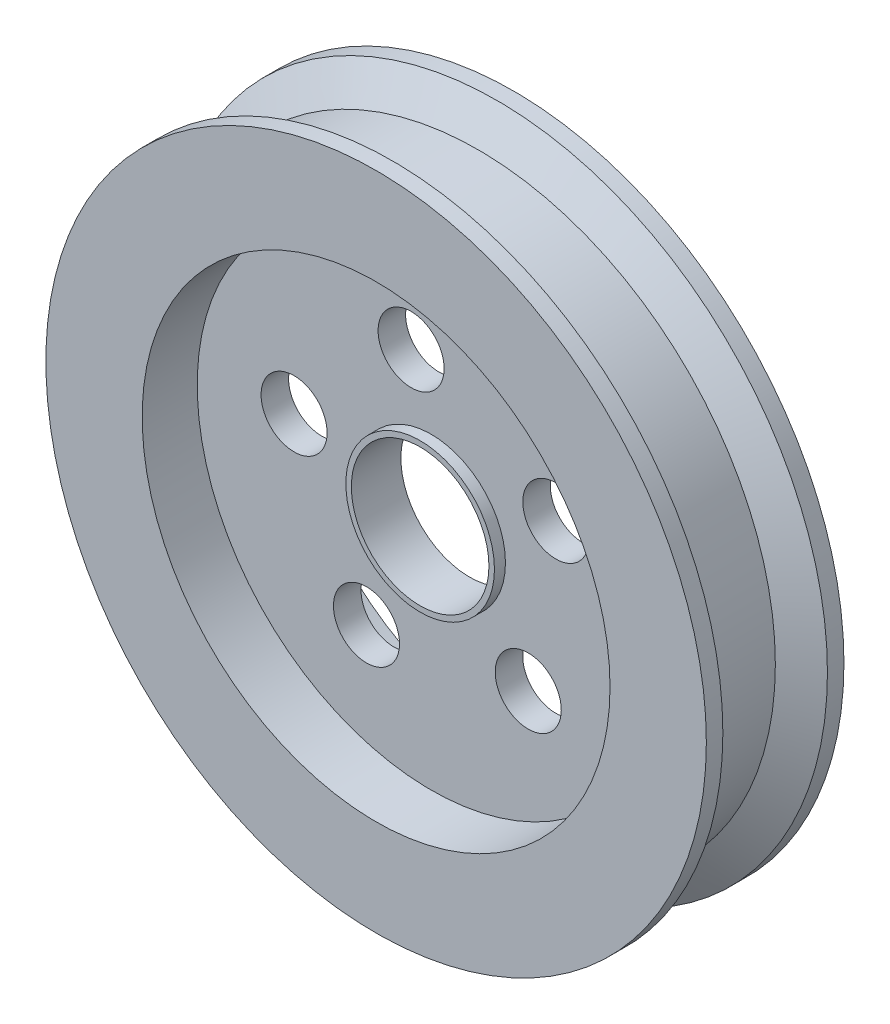
SolidWorks part; units mm, degrees
ref_plane "Front Plane" through (0, 0, 0) normal (0, 0, 1) x (1, 0, 0)
ref_plane "Top Plane" through (0, 0, 0) normal (0, 1, 0) x (1, 0, 0)
ref_plane "Right Plane" through (0, 0, 0) normal (1, 0, 0) x (0, 0, -1)
sketch "Sketch1" plane through (0, 0, 0) normal (0, 0, 1) x (1, 0, 0)
  circle A0 centre (0, 0) radius 60
  circle A1 centre (0, 0) radius 12.5
  dimension "D1" = 120
  dimension "D2" = 25
extrude "Boss-Extrude1" add sketch "Sketch1" along normal mid plane 25
sketch "Sketch2" plane through (0, 0, 12.5) normal (0, 0, 1) x (1, 0, 0)
  circle A0 centre (0, 0) radius 42.5
  dimension "D1" = 85
extrude "Cut-Extrude1" cut sketch "Sketch2" against normal blind 10
mirror "Mirror1" about plane through (0, 0, 0) normal (0, 0, 1) of "Cut-Extrude1"
sketch "Sketch3" plane through (0, 0, 2.5) normal (0, 0, 1) x (1, 0, 0)
  circle A0 centre (-3.6394, 25) radius 6
  dimension "D1" = 12
  dimension "D2" = 25
extrude "Cut-Extrude2" cut sketch "Sketch3" against normal through all
pattern_circular "CirPattern2" count 5 over 360 about axis through (0, 0, 0) along (0, 0, 1) of "Cut-Extrude2"
sketch "Sketch5" plane through (0, 0, 0) normal (0, 1, 0) x (1, 0, 0)
  line L0 (0, 0) -> (0, 23.5811) construction
  line L1 (-60, 9.5) -> (-54, 6.0359)
  line L2 (-60, 12.5) -> (-60, -12.5) construction
  line L3 (-54, 6.0359) -> (-54, -6.0359)
  line L4 (-54, -6.0359) -> (-60, -9.5)
  line L5 (-60, -9.5) -> (-60, 9.5)
  dimension "D1" = 3
  dimension "D2" = 3
  dimension "D3" = 60
  dimension "D4" = 60
  dimension "D5" = 6
revolve "Cut-Revolve1" cut sketch "Sketch5" angle 360 about L0
sketch "Sketch6" plane through (0, 0, 2.5) normal (0, 0, 1) x (1, 0, 0)
  circle A0 centre (0, 0) radius 13.5
  circle A1 centre (0, 0) radius 12.5 construction
  circle A2 centre (0, 0) radius 12.5
  dimension "D1" = 27
extrude "Boss-Extrude2" add sketch "Sketch6" along normal blind 2 and the other way blind 7
